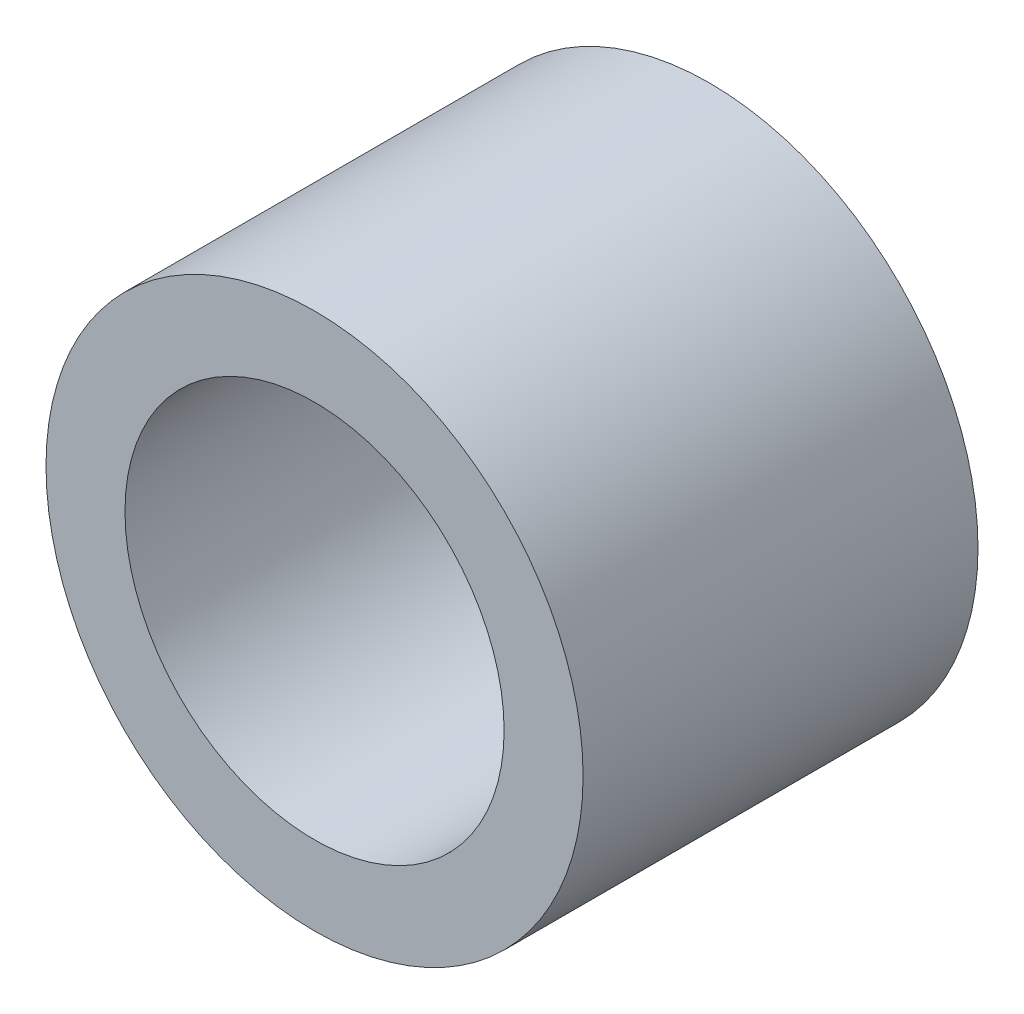
SolidWorks part; units mm, degrees
material "Phosphor bronze 10% D, UNS C52400"
ref_plane "Front Plane" through (0, 0, 0) normal (0, 0, 1) x (1, 0, 0)
ref_plane "Top Plane" through (0, 0, 0) normal (0, 1, 0) x (1, 0, 0)
ref_plane "Right Plane" through (0, 0, 0) normal (1, 0, 0) x (0, 0, -1)
sketch "Sketch1" plane through (0, 0, 0) normal (0, 0, 1) x (1, 0, 0)
  circle A0 centre (0, 0) radius 17
  circle A1 centre (0, 0) radius 12
  dimension "D1" = 34
  dimension "D2" = 24
extrude "Boss-Extrude1" add sketch "Sketch1" along normal blind 25
